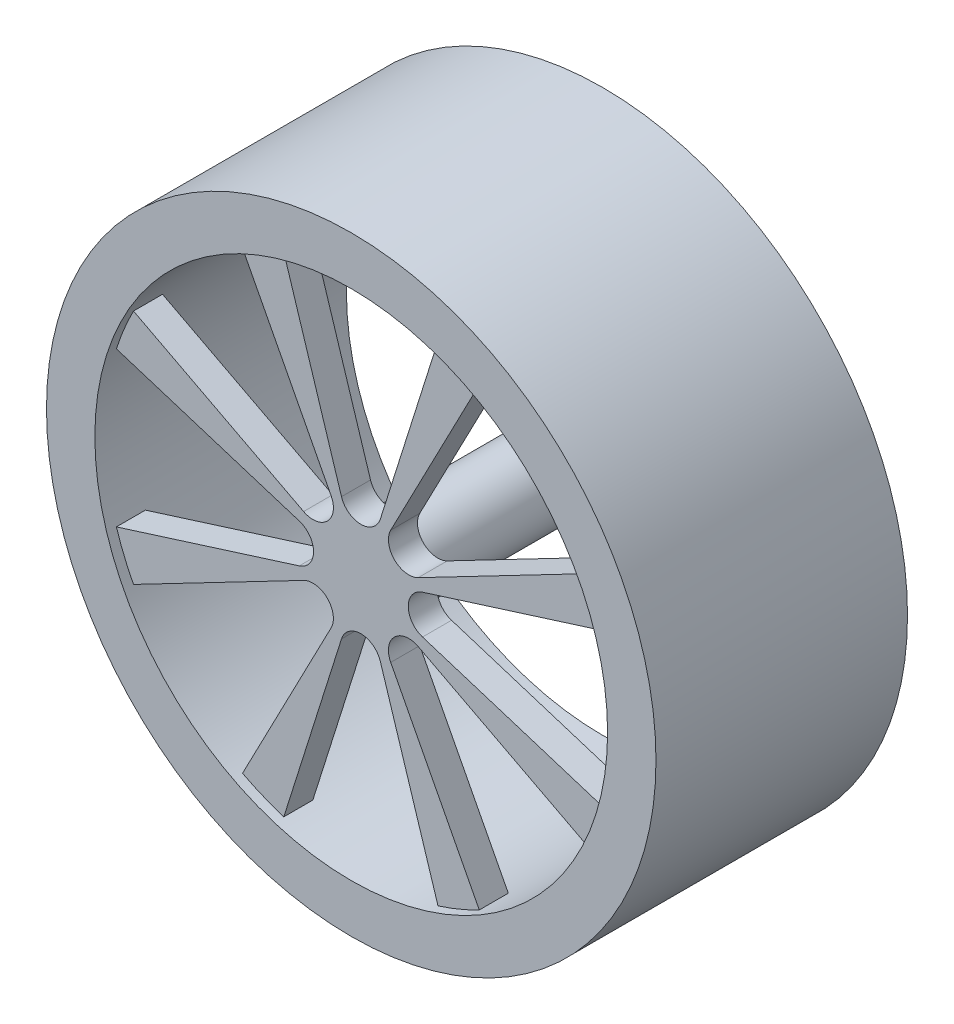
SolidWorks part; units mm, degrees
ref_plane "Plan de face" through (0, 0, 0) normal (0, 0, 1) x (1, 0, 0)
ref_plane "Plan de dessus" through (0, 0, 0) normal (0, 1, 0) x (1, 0, 0)
ref_plane "Plan de droite" through (0, 0, 0) normal (1, 0, 0) x (0, 0, -1)
sketch "Esquisse1" plane through (0, 0, 0) normal (0, 0, 1) x (1, 0, 0)
  circle A0 centre (0, 0) radius 31.5
  dimension "D1" = 63
extrude "Boss.-Extru.1" add sketch "Esquisse1" along normal blind 26
sketch "Esquisse2" plane through (0, 0, 26) normal (0, 0, 1) x (1, 0, 0)
  circle A0 centre (0, 0) radius 26.5
  circle A1 centre (0, 0) radius 31.5
  circle A2 centre (0, 0) radius 31.5
  dimension "D1" = 0
  dimension "D2" = 5
extrude "Enlèv. mat.-Extru.1" cut sketch "Esquisse2" against normal blind 1 contours A0
ref_plane "Plan1" through (0, 0, 13) normal (0, 0, 1) x (1, 0, 0)
mirror "Symétrie1" about plane through (0, 0, 13) normal (0, 0, 1) of "Enlèv. mat.-Extru.1"
sketch "Esquisse3" plane through (0, 0, 25) normal (0, 0, 1) x (1, 0, 0)
  line L0 (-7.9687, 25.2735) -> (-2.0075, 6.367)
  line L1 (2.0075, 6.367) -> (7.9687, 25.2735)
  line L2 (12.2363, 23.5058) -> (3.0826, 5.9217)
  line L3 (5.9217, 3.0826) -> (23.5058, 12.2363)
  line L4 (25.2735, 7.9687) -> (6.367, 2.0075)
  line L5 (6.367, -2.0075) -> (25.2735, -7.9687)
  line L6 (23.5058, -12.2363) -> (5.9217, -3.0826)
  line L7 (3.0826, -5.9217) -> (12.2363, -23.5058)
  line L8 (7.9687, -25.2735) -> (2.0075, -6.367)
  line L9 (-2.0075, -6.367) -> (-7.9687, -25.2735)
  line L10 (-12.2363, -23.5058) -> (-3.0826, -5.9217)
  line L11 (-5.9217, -3.0826) -> (-23.5058, -12.2363)
  line L12 (-25.2735, -7.9687) -> (-6.367, -2.0075)
  line L13 (-6.367, 2.0075) -> (-25.2735, 7.9687)
  line L14 (-23.5058, 12.2363) -> (-5.9217, 3.0826)
  line L15 (-3.0826, 5.9217) -> (-12.2363, 23.5058)
  circle A0 centre (0, 0) radius 26.5 construction
  circle A1 centre (0, 0) radius 26.5
  arc A2 (-2.0075, 6.367) -> (2.0075, 6.367) centre (0, 7) ccw
  circle A3 centre (0, 0) radius 26.5 construction
  circle A4 centre (0, 0) radius 26.5
  arc A5 (3.0826, 5.9217) -> (5.9217, 3.0826) centre (4.9497, 4.9497) ccw
  circle A6 centre (0, 0) radius 26.5
  arc A7 (6.367, 2.0075) -> (6.367, -2.0075) centre (7, 0) ccw
  circle A8 centre (0, 0) radius 26.5
  arc A9 (5.9217, -3.0826) -> (3.0826, -5.9217) centre (4.9497, -4.9497) ccw
  circle A10 centre (0, 0) radius 26.5
  arc A11 (2.0075, -6.367) -> (-2.0075, -6.367) centre (0, -7) ccw
  circle A12 centre (0, 0) radius 26.5
  arc A13 (-3.0826, -5.9217) -> (-5.9217, -3.0826) centre (-4.9497, -4.9497) ccw
  circle A14 centre (0, 0) radius 26.5
  arc A15 (-6.367, -2.0075) -> (-6.367, 2.0075) centre (-7, 0) ccw
  circle A16 centre (0, 0) radius 26.5
  arc A17 (-5.9217, 3.0826) -> (-3.0826, 5.9217) centre (-4.9497, 4.9497) ccw
  point P55 (0, 0)
  circle M5 centre (0, 0) radius 26.5
  dimension "D1" = 7
  dimension "D2" = 35
  dimension "D3" = 8
extrude "Enlèv. mat.-Extru.2" cut sketch "Esquisse3" against normal through all contours L0 A2 L1 M5 | L14 A17 L15 M5 | L12 A15 L13 M5 | L10 A13 L11 M5 | L8 A11 L9 M5 | L6 A9 L7 M5 | L4 A7 L5 M5 | L2 A5 L3 M5
sketch "Esquisse4" plane through (0, 0, 1) normal (0, 0, -1) x (-1, 0, 0)
  circle A0 centre (0, 0) radius 26.5 construction
  circle A1 centre (0, 0) radius 26.5
extrude "Enlèv. mat.-Extru.3" cut sketch "Esquisse4" against normal blind 21
sketch "Esquisse5" plane through (0, 0, 22) normal (0, 0, -1) x (-1, 0, 0)
  circle A0 centre (0, 0) radius 4
  dimension "D1" = 8
extrude "Boss.-Extru.2" add sketch "Esquisse5" along normal up to surface (22 mm away) up to face at (26.5, 0, 0)
sketch "Esquisse6" plane through (0, 0, 0) normal (0, 0, -1) x (-1, 0, 0)
  circle A0 centre (0, 0) radius 2
  dimension "D1" = 4
extrude "Enlèv. mat.-Extru.4" cut sketch "Esquisse6" against normal blind 5
